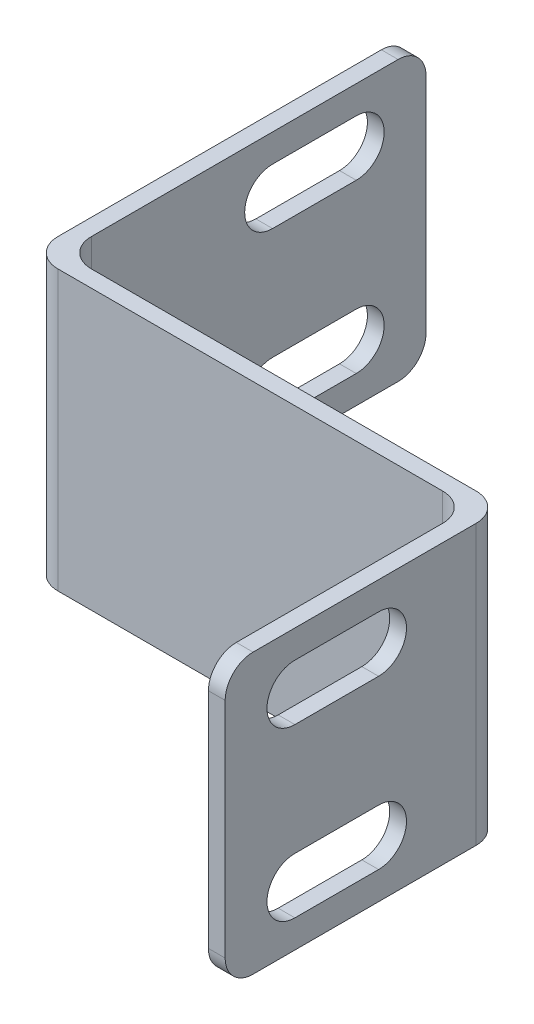
SolidWorks part; units mm, degrees
ref_plane "Front Plane" through (0, 0, 0) normal (0, 0, 1) x (1, 0, 0)
ref_plane "Top Plane" through (0, 0, 0) normal (0, 1, 0) x (1, 0, 0)
ref_plane "Right Plane" through (0, 0, 0) normal (1, 0, 0) x (0, 0, -1)
sketch "Sketch1" plane through (0, 0, 0) normal (0, 1, 0) x (1, 0, 0)
  line L0 (0, 0) -> (0, -65)
  line L1 (0, -65) -> (79, -65)
  line L2 (79, -65) -> (79, -115)
  line L3 (-3, 0) -> (-3, -68)
  line L4 (-3, -68) -> (76, -68)
  line L5 (76, -68) -> (76, -115)
  line L6 (0, 0) -> (-3, 0)
  line L7 (76, -115) -> (79, -115)
  dimension "D1" = 65
  dimension "D2" = 79
  dimension "D3" = 50
  dimension "D4" = 3
extrude "Boss-Extrude1" add sketch "Sketch1" along normal blind 50
fillet "Fillet1" radius 5 4 edges at (79, 25, 65) (76, 25, 68) (-3, 25, 68) (0, 25, 65)
sketch "Sketch2" plane through (76, 0, 0) normal (-1, 0, 0) x (0, 0, 1)
  line L0 (87.5, 40) -> (102.5, 40) construction
  line L1 (87.5, 45) -> (102.5, 45)
  line L2 (87.5, 35) -> (102.5, 35)
  line L3 (73, 50) -> (115, 50) construction
  line L4 (87.5, 10) -> (102.5, 10) construction
  line L5 (87.5, 15) -> (102.5, 15)
  line L6 (87.5, 5) -> (102.5, 5)
  line L7 (115, 50) -> (115, 0) construction
  arc A0 (87.5, 45) -> (87.5, 35) centre (87.5, 40) ccw
  arc A1 (102.5, 35) -> (102.5, 45) centre (102.5, 40) ccw
  arc A2 (87.5, 15) -> (87.5, 5) centre (87.5, 10) ccw
  arc A3 (102.5, 5) -> (102.5, 15) centre (102.5, 10) ccw
  point P2 (95, 40)
  point P13 (95, 10)
  dimension "D2" = 5
  dimension "D4" = 2
  dimension "D1" = 15
  dimension "D3" = 10
  dimension "D5" = 20
extrude "Cut-Extrude1" cut sketch "Sketch2" against normal up to surface (3 mm away) up to face at (79, 25, 92.5)
sketch "Sketch3" plane through (-3, 0, 0) normal (-1, 0, 0) x (0, 0, 1)
  line L0 (12.5, 40) -> (27.5, 40) construction
  line L1 (12.5, 45) -> (27.5, 45)
  line L2 (12.5, 35) -> (27.5, 35)
  line L3 (0, 50) -> (63, 50) construction
  line L4 (0, 50) -> (0, 0) construction
  line L5 (12.5, 10) -> (27.5, 10) construction
  line L6 (12.5, 15) -> (27.5, 15)
  line L7 (12.5, 5) -> (27.5, 5)
  arc A0 (12.5, 45) -> (12.5, 35) centre (12.5, 40) ccw
  arc A1 (27.5, 35) -> (27.5, 45) centre (27.5, 40) ccw
  arc A2 (12.5, 15) -> (12.5, 5) centre (12.5, 10) ccw
  arc A3 (27.5, 5) -> (27.5, 15) centre (27.5, 10) ccw
  point P2 (20, 40)
  point P14 (20, 10)
  dimension "D1" = 15
  dimension "D2" = 10
  dimension "D3" = 10
  dimension "D4" = 20
  dimension "D5" = 2
extrude "Cut-Extrude2" cut sketch "Sketch3" against normal up to surface (3 mm away) up to face at (0, 25, 30)
fillet "Fillet2" radius 5 4 edges at (77.5, 0, 115) (77.5, 50, 115) (-1.5, 0, 0) (-1.5, 50, 0)
